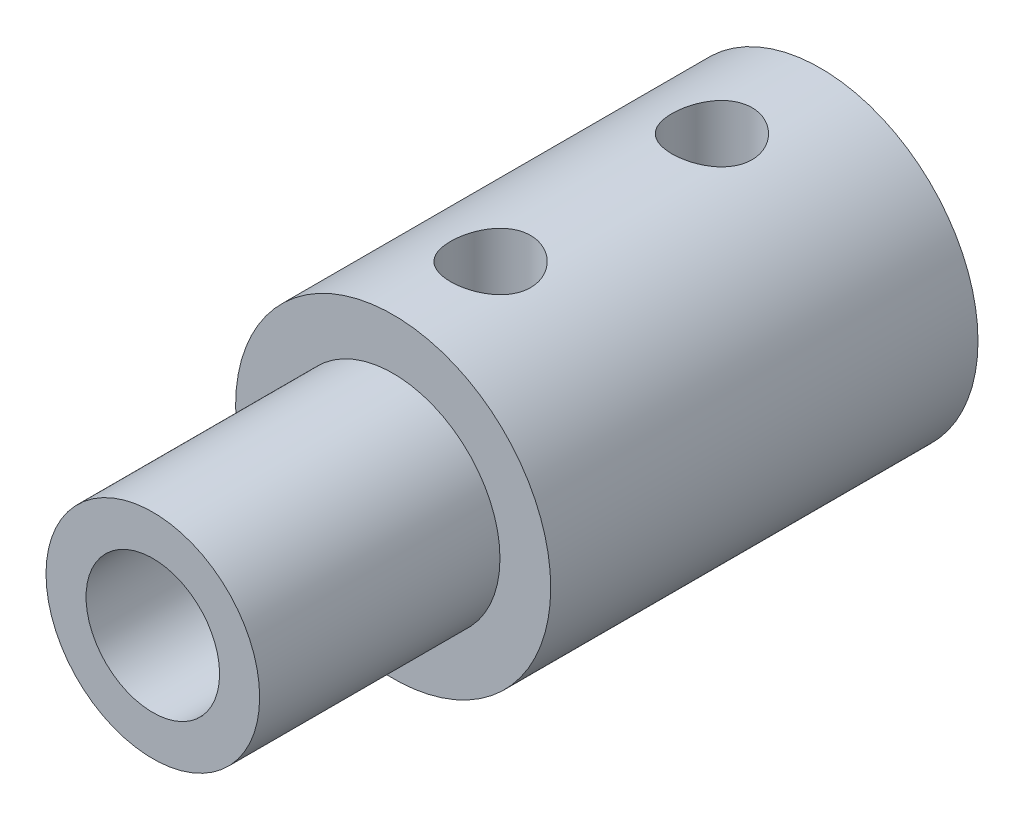
SolidWorks part; units mm, degrees
ref_plane "Спереди" through (0, 0, 0) normal (0, 0, 1) x (1, 0, 0)
ref_plane "Сверху" through (0, 0, 0) normal (0, 1, 0) x (1, 0, 0)
ref_plane "Справа" through (0, 0, 0) normal (1, 0, 0) x (0, 0, -1)
sketch "Эскиз1" plane through (0, 0, 0) normal (0, 0, 1) x (1, 0, 0)
  circle A0 centre (0, 0) radius 5.9
extrude "Вытянуть1" add sketch "Эскиз1" along normal blind 25
sketch "Эскиз2" plane through (0, 0, 25) normal (0, 0, 1) x (1, 0, 0)
  circle A0 centre (0, 0) radius 2.5
extrude "Вытянуть2" cut sketch "Эскиз2" against normal blind 10
sketch "Эскиз3" plane through (0, 0, 0) normal (0, 0, -1) x (-1, 0, 0)
  circle A0 centre (0, 0) radius 1.5
extrude "Вытянуть3" cut sketch "Эскиз3" against normal blind 15
ref_plane "Плоскость1" through (0, 7, 0) normal (0, 1, 0) x (-1, 0, 0)
sketch "Эскиз5" plane through (0, 7, 0) normal (0, 1, 0) x (-1, 0, 0)
  circle A0 centre (0, 4.0632) radius 1.5
  circle A1 centre (0, 12.3526) radius 1.5
extrude "Вытянуть4" cut sketch "Эскиз5" against normal blind 6
sketch "Эскиз6" plane through (0, 0, 25) normal (0, 0, 1) x (1, 0, 0)
  circle A0 centre (0, 0) radius 5.9
  circle A1 centre (0, 0) radius 4
extrude "Вытянуть5" cut sketch "Эскиз6" against normal blind 9
